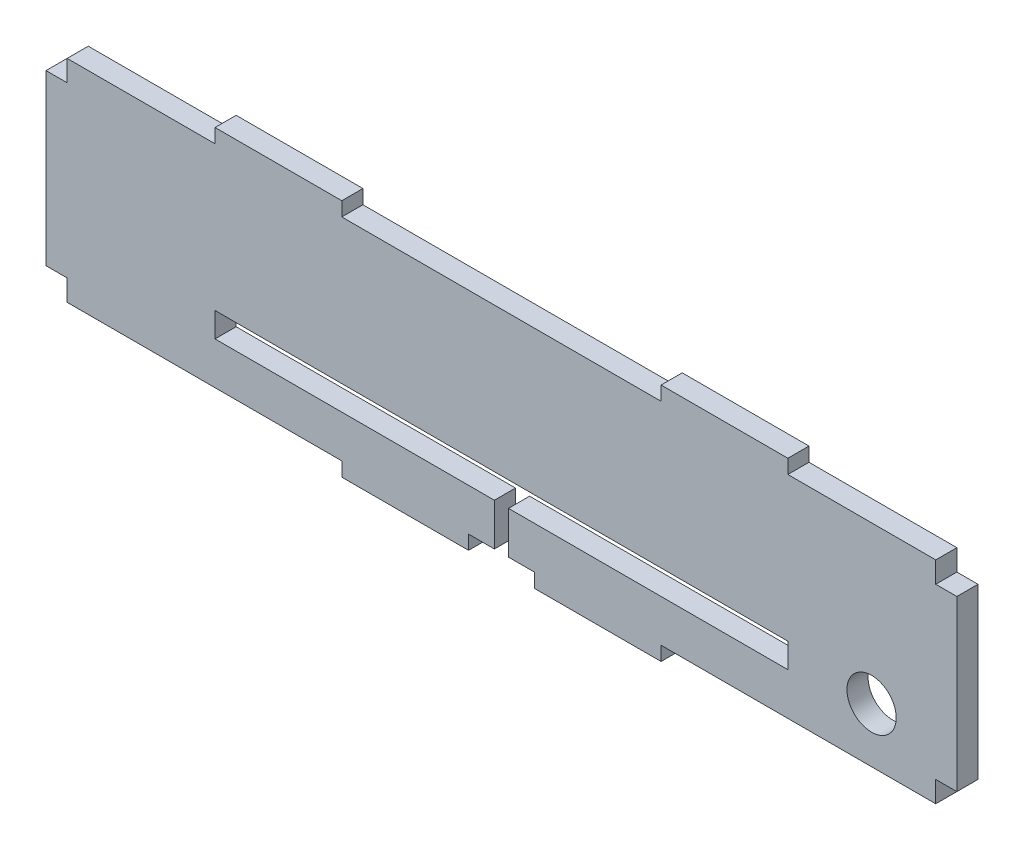
SolidWorks part; units mm, degrees
ref_plane "Front Plane" through (0, 0, 0) normal (0, 0, 1) x (1, 0, 0)
ref_plane "Top Plane" through (0, 0, 0) normal (0, 1, 0) x (1, 0, 0)
ref_plane "Right Plane" through (0, 0, 0) normal (1, 0, 0) x (0, 0, -1)
sketch "Sketch1" plane through (0, 0, 0) normal (0, 0, 1) x (1, 0, 0)
  line L0 (0, 0) -> (0, 43717.3993) construction
  line L1 (-5.9695, 0) -> (43711.4297, 0) construction
  line L2 (0, 0) -> (42, 0)
  line L4 (0, 0) -> (0, 30)
  line L6 (129.34, 0) -> (129.34, 30)
  line L7 (42, 0) -> (42, -2)
  line L8 (42, -2) -> (60, -2)
  line L9 (60, -2) -> (60, 0)
  line L10 (60, 0) -> (69.34, 0)
  line L11 (69.34, 0) -> (69.34, -2)
  line L12 (69.34, -2) -> (87.34, -2)
  line L13 (87.34, -2) -> (87.34, 0)
  line L14 (87.34, 0) -> (129.34, 0)
  line L15 (64.67, 0) -> (64.67, -50000) construction
  line L16 (24, 9.5) -> (105.34, 9.5)
  line L17 (24, 9.5) -> (24, 6)
  line L19 (105.34, 9.5) -> (105.34, 6)
  line L20 (65.67, 0) -> (65.67, 6)
  line L21 (63.67, 0) -> (65.67, 0)
  line L22 (63.67, 0) -> (63.67, 6)
  line L25 (24, 6) -> (63.67, 6)
  line L26 (65.67, 6) -> (105.34, 6)
  line L27 (0, 30) -> (24, 30)
  line L29 (42, 30) -> (42, 32)
  line L30 (42, 32) -> (24, 32)
  line L31 (24, 30) -> (24, 32)
  line L32 (42, 30) -> (87.34, 30)
  line L33 (129.34, 30) -> (105.34, 30)
  line L34 (105.34, 30) -> (105.34, 32)
  line L35 (87.34, 32) -> (105.34, 32)
  line L36 (87.34, 30) -> (87.34, 32)
  line L37 (129.34, 3) -> (126.34, 3)
  line L38 (0, 0) -> (3, 0)
  line L39 (0, 0) -> (0, 3)
  line L40 (0, 3) -> (3, 3)
  line L41 (3, 0) -> (3, 3)
  line L42 (126.34, 0) -> (126.34, 3)
  line L43 (129.34, 0) -> (126.34, 0)
  line L44 (129.34, 0) -> (129.34, 3)
  line L45 (-14.82, 15) -> (49985.18, 15) construction
  line L46 (129.34, 30) -> (126.34, 30)
  line L47 (126.34, 30) -> (126.34, 27)
  line L48 (129.34, 27) -> (126.34, 27)
  line L49 (129.34, 30) -> (129.34, 27)
  line L50 (0, 27) -> (3, 27)
  line L51 (3, 30) -> (3, 27)
  line L52 (0, 30) -> (3, 30)
  line L53 (0, 30) -> (0, 27)
  circle A0 centre (117.2288, 7.75) radius 3.5
  point P36 (64.67, 30)
  point P51 (0, 0)
  point P52 (0, 0)
  dimension "D15" = 7.75
  dimension "D27" = 7
  dimension "D1" = 129.34
  dimension "D2" = 30
  dimension "D3" = 18
  dimension "D4" = 18
  dimension "D5" = 42
  dimension "D6" = 42
  dimension "D7" = 2
  dimension "D8" = 2
  dimension "D9" = 24
  dimension "D10" = 24
  dimension "D11" = 6
  dimension "D12" = 3.5
  dimension "D13" = 15
  dimension "D14" = 2
  dimension "D16" = 3
  dimension "D17" = 21
  dimension "D18" = 18
  dimension "D19" = 45.34
  dimension "D20" = 18
  dimension "D21" = 21
  dimension "D22" = 3
  dimension "D23" = 3
  dimension "D24" = 20.5
  dimension "D25" = 3
  dimension "D26" = 9.34
  dimension "D28" = 2
extrude "Boss-Extrude3" add sketch "Sketch1" along normal blind 3 contours L36 L32 L29 L30 L31 L27 L4 L2 L7 L8 L9 L10 L22 L25 L17 L16 L19 L26 L20 L11 L12 L13 L14 L6 L33 L34 L35
